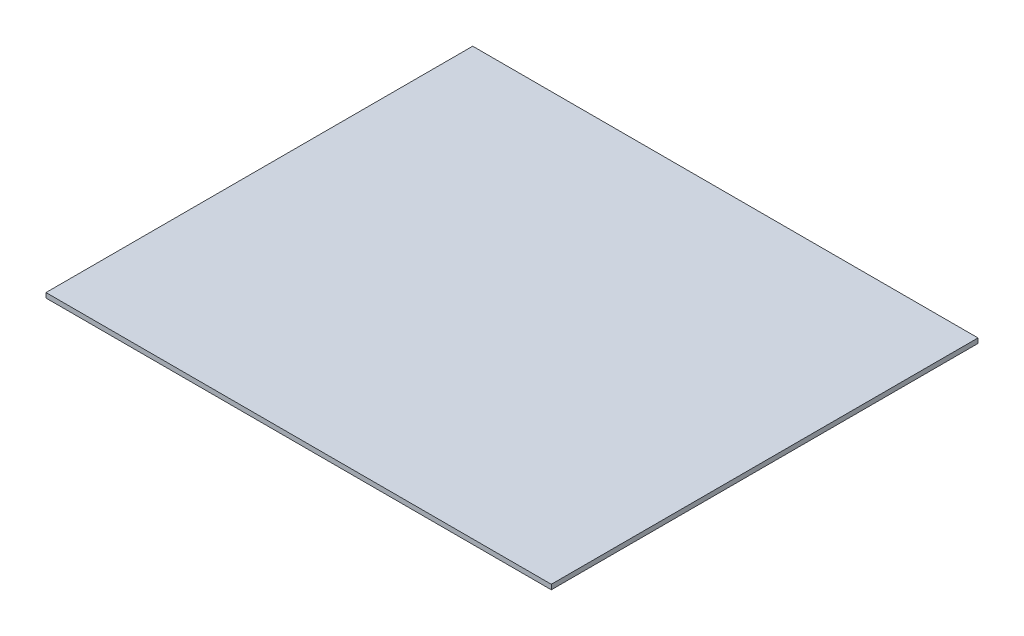
SolidWorks part; units mm, degrees
ref_plane "Front Plane" through (0, 0, 0) normal (0, 0, 1) x (1, 0, 0)
ref_plane "Top Plane" through (0, 0, 0) normal (0, 1, 0) x (1, 0, 0)
ref_plane "Right Plane" through (0, 0, 0) normal (1, 0, 0) x (0, 0, -1)
sketch "Sketch1" plane through (0, 0, 0) normal (0, 1, 0) x (1, 0, 0)
  line L1 (-157.5, -133) -> (157.5, -133)
  line L2 (-157.5, -133) -> (-157.5, 133)
  line L3 (-157.5, 133) -> (157.5, 133)
  line L4 (157.5, -133) -> (157.5, 133)
  line L5 (-157.5, -133) -> (157.5, 133) construction
  line L6 (-157.5, 133) -> (157.5, -133) construction
  point P0 (0, 0)
  dimension "D1" = 266
  dimension "D2" = 315
extrude "Boss-Extrude1" add sketch "Sketch1" along normal blind 3 contours L3 L4 L1 L2
sketch "Sketch2" plane through (0, 0, 0) normal (0, -1, 0) x (1, 0, 0)
  line L0 (0, 0) -> (0, -133) construction
  line L1 (-157.5, -133) -> (157.5, -133) construction
  line L2 (0, -133) -> (-157.5, -133) construction
  line L3 (-102.25, -98) -> (-102.25, -133)
  line L4 (-102.25, -133) -> (-52.25, -133)
  line L5 (-52.25, -133) -> (-52.25, -98)
  line L6 (-52.25, -98) -> (-102.25, -98)
  line L7 (-102.25, -115.5) -> (-52.25, -115.5) construction
  line L8 (-77.25, -133) -> (-77.25, -115.5) construction
  line L9 (-77.25, -115.5) -> (-77.25, -98) construction
  point P15 (0, 0)
  dimension "D1" = 35
  dimension "D2" = 50
  dimension "D3" = 77.25
extrude "Cut-Extrude1" cut sketch "Sketch2" against normal blind 2
mirror "Mirror1" about plane through (0, 0, 0) normal (1, 0, 0) of "Cut-Extrude1"
